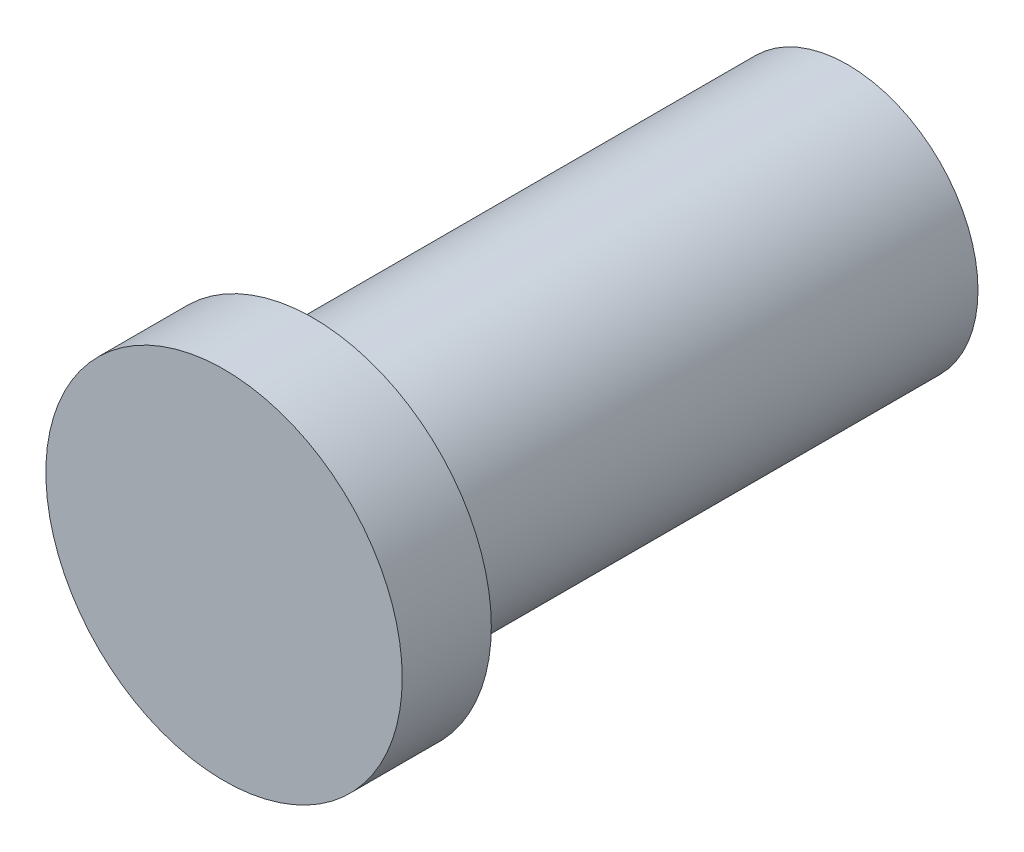
SolidWorks part; units mm, degrees
ref_plane "Plan de face" through (0, 0, 0) normal (0, 0, 1) x (1, 0, 0)
ref_plane "Plan de dessus" through (0, 0, 0) normal (0, 1, 0) x (1, 0, 0)
ref_plane "Plan de droite" through (0, 0, 0) normal (1, 0, 0) x (0, 0, -1)
sketch "Esquisse1" plane through (0, 0, 0) normal (0, 0, 1) x (1, 0, 0)
  circle A0 centre (-7.5972, 3.919) radius 2.925
extrude "Boss.-Extru.1" add sketch "Esquisse1" along normal blind 12
sketch "Esquisse2" plane through (0, 0, 12) normal (0, 0, 1) x (1, 0, 0)
  circle A0 centre (-7.5972, 3.919) radius 4
extrude "Boss.-Extru.2" add sketch "Esquisse2" along normal blind 2
